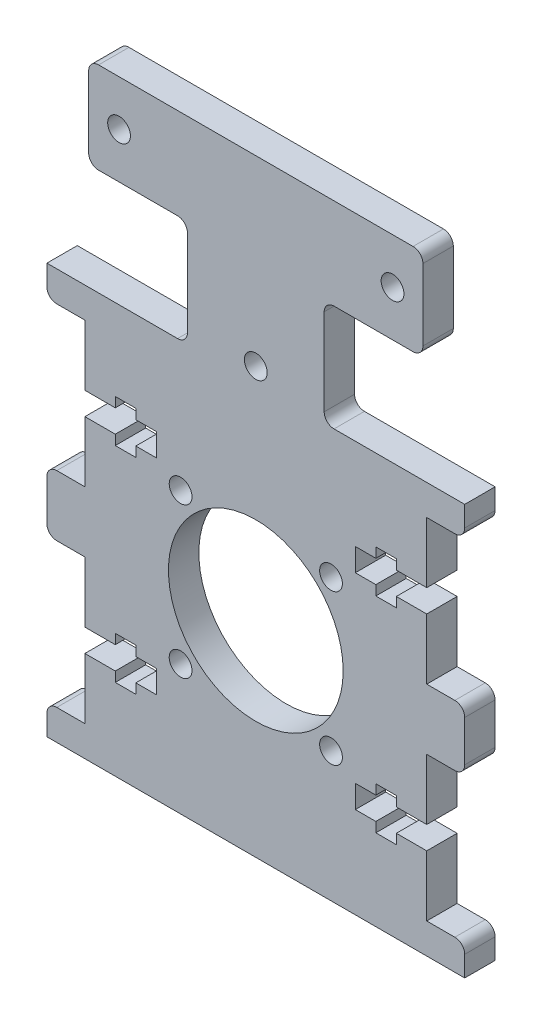
SolidWorks part; units mm, degrees
ref_plane "前视基准面" through (0, 0, 0) normal (0, 0, 1) x (1, 0, 0)
ref_plane "上视基准面" through (0, 0, 0) normal (0, 1, 0) x (1, 0, 0)
ref_plane "右视基准面" through (0, 0, 0) normal (1, 0, 0) x (0, 0, -1)
sketch "草图1" plane through (0, 0, 0) normal (0, 0, 1) x (1, 0, 0)
  line L0 (-22.5, 0) -> (-24.9483, 0) construction
  line L1 (22.5, -27) -> (-22.5, -27)
  line L3 (22.5, 27) -> (-22.5, 27) construction
  line L4 (-22.5, -27) -> (-22.5, 27) construction
  line L5 (22.5, -27) -> (-22.5, 27) construction
  line L6 (22.5, 27) -> (-22.5, -27) construction
  line L7 (-22.5, 4) -> (-27.5, 4)
  line L8 (-27.5, 4) -> (-27.5, -4)
  line L9 (-27.5, -4) -> (-22.5, -4)
  line L10 (-22.5, 15) -> (-18.5, 15)
  line L11 (-18.5, 15) -> (-18.5, 16.3)
  line L12 (-18.5, 16.3) -> (-15.8, 16.3)
  line L13 (-15.8, 16.3) -> (-15.8, 15)
  line L14 (-15.8, 15) -> (-13.1, 15)
  line L15 (-13.1, 15) -> (-13.1, 12)
  line L16 (-13.1, 12) -> (-15.8, 12)
  line L17 (-15.8, 12) -> (-15.8, 10.7)
  line L18 (-15.8, 10.7) -> (-18.5, 10.7)
  line L19 (-18.5, 10.7) -> (-18.5, 12)
  line L20 (-18.5, 12) -> (-22.5, 12)
  line L21 (-18.5, -12) -> (-22.5, -12)
  line L22 (-18.5, -10.7) -> (-18.5, -12)
  line L23 (-15.8, -10.7) -> (-18.5, -10.7)
  line L24 (-15.8, -12) -> (-15.8, -10.7)
  line L25 (-13.1, -12) -> (-15.8, -12)
  line L26 (-13.1, -15) -> (-13.1, -12)
  line L27 (-15.8, -15) -> (-13.1, -15)
  line L28 (-15.8, -16.3) -> (-15.8, -15)
  line L29 (-18.5, -16.3) -> (-15.8, -16.3)
  line L30 (-18.5, -15) -> (-18.5, -16.3)
  line L31 (-22.5, -15) -> (-18.5, -15)
  line L32 (-22.5, -23) -> (-27.5, -23)
  line L33 (-27.5, -23) -> (-27.5, -27)
  line L34 (-27.5, -27) -> (-22.5, -27)
  line L35 (-27.5, 23) -> (-27.5, 27)
  line L36 (-22.5, 23) -> (-27.5, 23)
  line L37 (-27.5, 27) -> (-22.5, 27)
  line L38 (0, 0) -> (0, -4) construction
  line L39 (22.5, -27) -> (22.5, 27) construction
  line L40 (22.5, 0) -> (24.9483, 0) construction
  line L41 (27.5, 27) -> (22.5, 27)
  line L42 (22.5, 23) -> (27.5, 23)
  line L43 (27.5, 23) -> (27.5, 27)
  line L44 (27.5, -27) -> (22.5, -27)
  line L45 (27.5, -23) -> (27.5, -27)
  line L46 (22.5, -23) -> (27.5, -23)
  line L47 (22.5, -15) -> (18.5, -15)
  line L48 (18.5, -15) -> (18.5, -16.3)
  line L49 (18.5, -16.3) -> (15.8, -16.3)
  line L50 (15.8, -16.3) -> (15.8, -15)
  line L51 (15.8, -15) -> (13.1, -15)
  line L52 (13.1, -15) -> (13.1, -12)
  line L53 (13.1, -12) -> (15.8, -12)
  line L54 (15.8, -12) -> (15.8, -10.7)
  line L55 (15.8, -10.7) -> (18.5, -10.7)
  line L56 (18.5, -10.7) -> (18.5, -12)
  line L57 (18.5, -12) -> (22.5, -12)
  line L58 (18.5, 12) -> (22.5, 12)
  line L59 (18.5, 10.7) -> (18.5, 12)
  line L60 (15.8, 10.7) -> (18.5, 10.7)
  line L61 (15.8, 12) -> (15.8, 10.7)
  line L62 (13.1, 12) -> (15.8, 12)
  line L63 (13.1, 15) -> (13.1, 12)
  line L64 (15.8, 15) -> (13.1, 15)
  line L65 (15.8, 16.3) -> (15.8, 15)
  line L66 (18.5, 16.3) -> (15.8, 16.3)
  line L67 (18.5, 15) -> (18.5, 16.3)
  line L68 (22.5, 15) -> (18.5, 15)
  line L69 (27.5, -4) -> (22.5, -4)
  line L70 (27.5, 4) -> (27.5, -4)
  line L71 (22.5, 4) -> (27.5, 4)
  line L72 (-22.5, 23) -> (-22.5, 15)
  line L73 (-22.5, 12) -> (-22.5, 4)
  line L74 (-22.5, -4) -> (-22.5, -12)
  line L75 (-22.5, -15) -> (-22.5, -23)
  line L76 (22.5, -23) -> (22.5, -15)
  line L77 (22.5, -12) -> (22.5, -4)
  line L78 (22.5, 4) -> (22.5, 12)
  line L79 (22.5, 23) -> (22.5, 15)
  line L80 (0, 0) -> (0, 47) construction
  line L81 (0, 47) -> (-18, 47) construction
  line L82 (22, 53) -> (-22, 53)
  line L83 (-22, 53) -> (-22, 41)
  line L84 (-22, 41) -> (-9, 41)
  line L85 (-9, 41) -> (-9, 27)
  line L86 (-9, 27) -> (-22.5, 27)
  line L87 (22, 53) -> (22, 41)
  line L88 (22, 41) -> (9, 41)
  line L89 (9, 41) -> (9, 27)
  line L90 (9, 27) -> (22.5, 27)
  circle A0 centre (0, 0) radius 14 construction
  circle A1 centre (9.8995, 9.8995) radius 1.5
  circle A5 centre (0, 0) radius 11.5
  circle A6 centre (9.8995, -9.8995) radius 1.5
  circle A7 centre (-9.8995, -9.8995) radius 1.5
  circle A8 centre (-9.8995, 9.8995) radius 1.5
  circle A9 centre (-18, 47) radius 1.5
  circle A10 centre (18, 47) radius 1.5
  circle A11 centre (0, 29) radius 1.5
  point P35 (-17.15, 10.7)
  point P48 (-21.5, -15)
  point P91 (21.5, -15)
  dimension "D2" = 23
  dimension "D12" = 3
  dimension "D17" = 28
  dimension "D21" = 18
  dimension "D22" = 18
  dimension "D27" = 3
  dimension "D3" = 45
  dimension "D4" = 54
  dimension "D5" = 8
  dimension "D6" = 5
  dimension "D7" = 4
  dimension "D8" = 8
  dimension "D9" = 2.7
  dimension "D10" = 4
  dimension "D11" = 3
  dimension "D13" = 5.6
  dimension "D14" = 4
  dimension "D15" = 5
  dimension "D16" = 8
  dimension "D19" = 29
  dimension "D20" = 18
  dimension "D23" = 13
  dimension "D24" = 12
  dimension "D25" = 6
  dimension "D26" = 4
  dimension "D18" = 4
extrude "凸台-拉伸1" add sketch "草图1" along normal blind 4
sketch "草图2" plane through (-22.5, 0, 0) normal (-1, 0, 0) x (0, 0, 1)
  line L0 (2, 15) -> (2, 12) construction
  line L1 (4, 15) -> (0, 15) construction
  line L2 (4, 12) -> (0, 12) construction
  line L3 (-0.15, 27.15) -> (4.15, 27.15) construction
  line L4 (4.15, -4.15) -> (-0.15, -4.15)
  line L5 (4.15, -4.15) -> (4.15, 4.15)
  line L6 (4.15, 4.15) -> (-0.15, 4.15)
  line L7 (-0.15, -4.15) -> (-0.15, 4.15)
  line L8 (4.15, -4.15) -> (-0.15, 4.15) construction
  line L9 (4.15, 4.15) -> (-0.15, -4.15) construction
  line L18 (4.15, 27.15) -> (4.15, 22.85)
  line L19 (-0.15, 22.85) -> (4.15, 22.85)
  line L20 (-0.15, 27.15) -> (-0.15, 22.85)
  line L21 (2, 0) -> (2.8697, 0) construction
  line L22 (-0.15, -27.15) -> (4.15, -27.15) construction
  line L23 (2, -15) -> (2, -12) construction
  line L24 (-0.15, -27.15) -> (-0.15, -22.85)
  line L25 (-0.15, -22.85) -> (4.15, -22.85)
  line L26 (4.15, -27.15) -> (4.15, -22.85)
  line L27 (4.15, -27.15) -> (8, -27.15)
  line L28 (8, -27.15) -> (8, 27.15)
  line L29 (8, 27.15) -> (4.15, 27.15)
  line L30 (-0.15, -27.15) -> (-64.002, -27.15)
  line L31 (-64.002, -27.15) -> (-64.002, 27.15)
  line L32 (-64.002, 27.15) -> (-0.15, 27.15)
  circle A0 centre (2, 13.5) radius 1.5
  circle A1 centre (2, -13.5) radius 1.5
  point P8 (2, 0)
  dimension "D1" = 8.3
  dimension "D2" = 4.3
sketch "草图3" plane through (22.5, 0, 0) normal (1, 0, 0) x (0, 0, -1)
  line L0 (-2, 12) -> (-2, 15)
  line L1 (-4, 12) -> (0, 12) construction
  line L2 (-4, 15) -> (0, 15) construction
  circle A0 centre (-2, 13.5) radius 1.5
fillet "圆角1" radius 1.3 16 edges at (-9, 27, 2) (9, 27, 2) (9, 41, 2) (-9, 41, 2) (22, 53, 2) (22, 41, 2) (-22, 53, 2) (-22, 41, 2) (-27.5, -23, 2) (-27.5, 23, 2) (-27.5, 4, 2) (-27.5, -4, 2) (27.5, -23, 2) (27.5, 4, 2) (27.5, -4, 2) (27.5, 23, 2)
